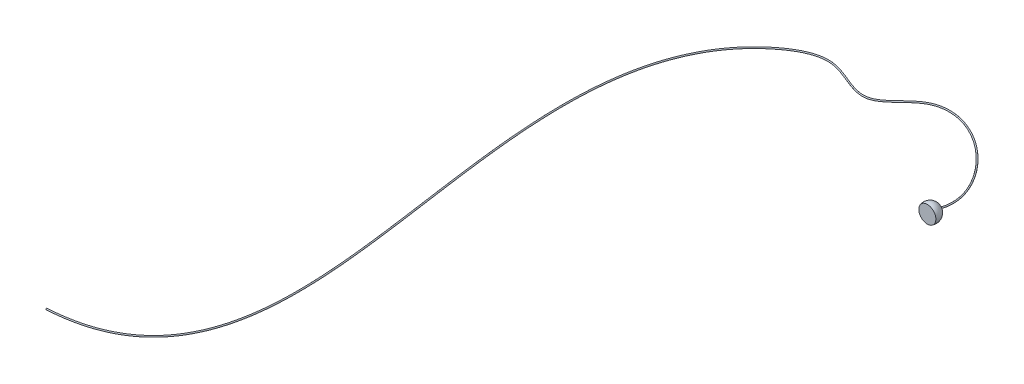
SolidWorks part; units mm, degrees
ref_plane "Front Plane" through (0, 0, 0) normal (0, 0, 1) x (1, 0, 0)
ref_plane "Top Plane" through (0, 0, 0) normal (0, 1, 0) x (1, 0, 0)
ref_plane "Right Plane" through (0, 0, 0) normal (1, 0, 0) x (0, 0, -1)
sketch "Sketch1" plane through (0, 0, 0) normal (0, 1, 0) x (1, 0, 0)
  line L0 (-2.3251, 5.08) -> (-1.8483, 5.08)
  line L1 (-1.8483, 5.08) -> (-1.8483, 5.7304)
  arc A0 (-2.3251, 5.08) -> (-1.8483, 5.7304) centre (-1.8483, 5.2304) cw
  dimension "D1" = 0.5
  dimension "D2" = 107.5
revolve "Revolve3" add sketch "Sketch1" angle 360 about L1
sketch "Sketch2" plane through (0, 0, 0) normal (0, 1, 0) x (1, 0, 0)
  spline S0 degree 3 poles (-1.8668, 5.5692) (-0.7809, 7.647) (-6.0712, 12.9223) (-9.0818, 8.1939) (-11.7411, 10.312) (-24.492, 3.2547) (-7.8459, -23.202) (-21.8275, -24.0523) knots 0 0 0 0 0.162085 0.208444 0.265294 0.314652 1 1 1 1
sweep "Sweep1" add path "Sketch2" circular profile diameter 0.07 parameters "D3"=0.07
